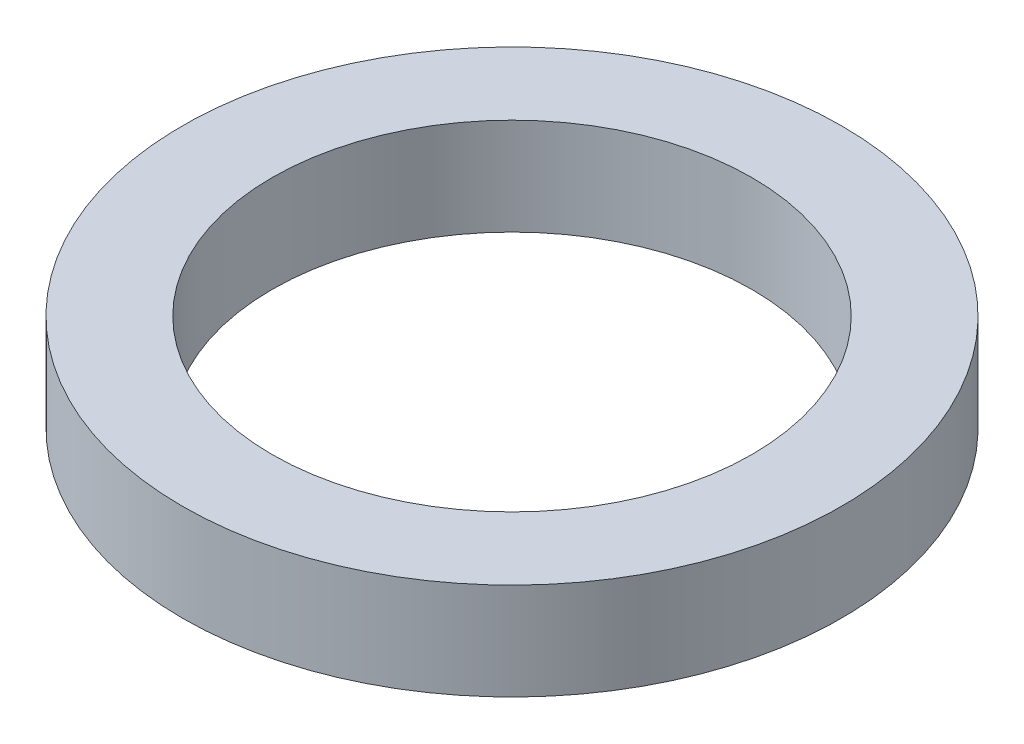
SolidWorks part; units mm, degrees
ref_plane "Front Plane" through (0, 0, 0) normal (0, 0, 1) x (1, 0, 0)
ref_plane "Top Plane" through (0, 0, 0) normal (0, 1, 0) x (1, 0, 0)
ref_plane "Right Plane" through (0, 0, 0) normal (1, 0, 0) x (0, 0, -1)
sketch "Sketch1" plane through (0, 0, 0) normal (0, 1, 0) x (1, 0, 0)
  circle A0 centre (0, 0) radius 13.6
  circle A1 centre (0, 0) radius 9.9
  dimension "D1" = 19.8
  dimension "D2" = 27.2
extrude "Boss-Extrude1" add sketch "Sketch1" along normal blind 4
